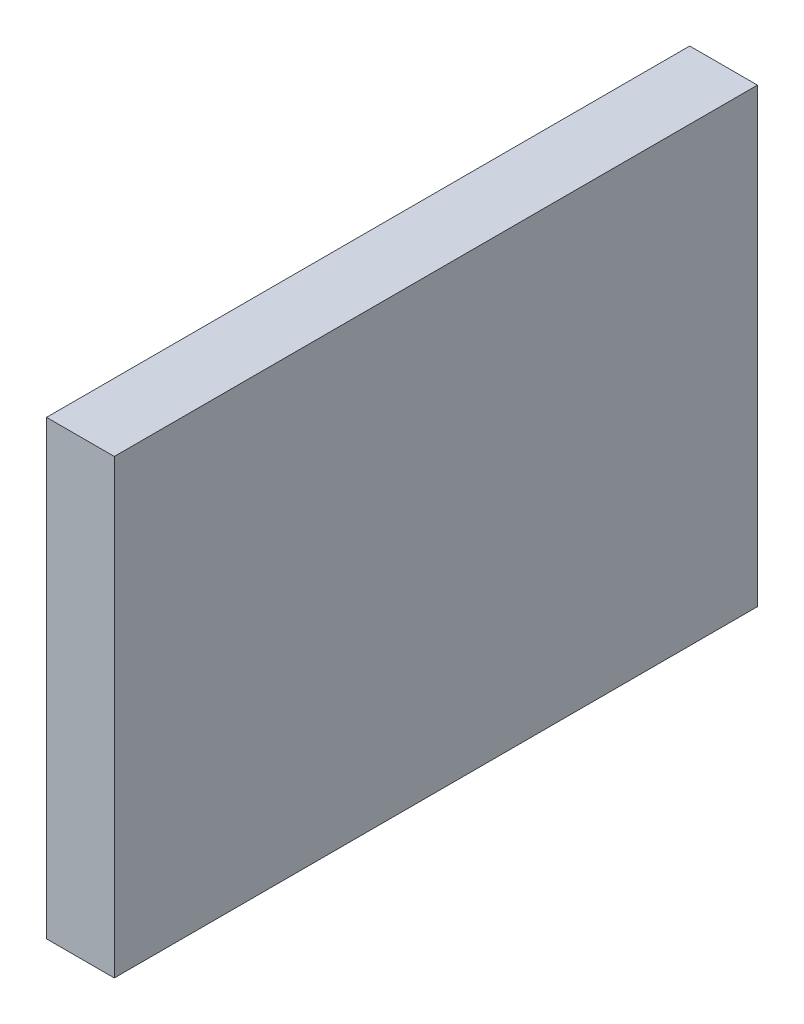
SolidWorks part; units mm, degrees
ref_plane "Alzado" through (0, 0, 0) normal (0, 0, 1) x (1, 0, 0)
ref_plane "Planta" through (0, 0, 0) normal (0, 1, 0) x (1, 0, 0)
ref_plane "Vista lateral" through (0, 0, 0) normal (1, 0, 0) x (0, 0, -1)
sketch "Croquis1" plane through (0, 0, 0) normal (1, 0, 0) x (0, 0, -1)
  line L1 (0, 0) -> (142.4, 0)
  line L2 (0, 0) -> (0, 100)
  line L3 (0, 100) -> (142.4, 100)
  line L4 (142.4, 0) -> (142.4, 100)
  dimension "D1" = 100
  dimension "D2" = 142.4
extrude "Saliente-Extruir1" add sketch "Croquis1" along normal blind 15
